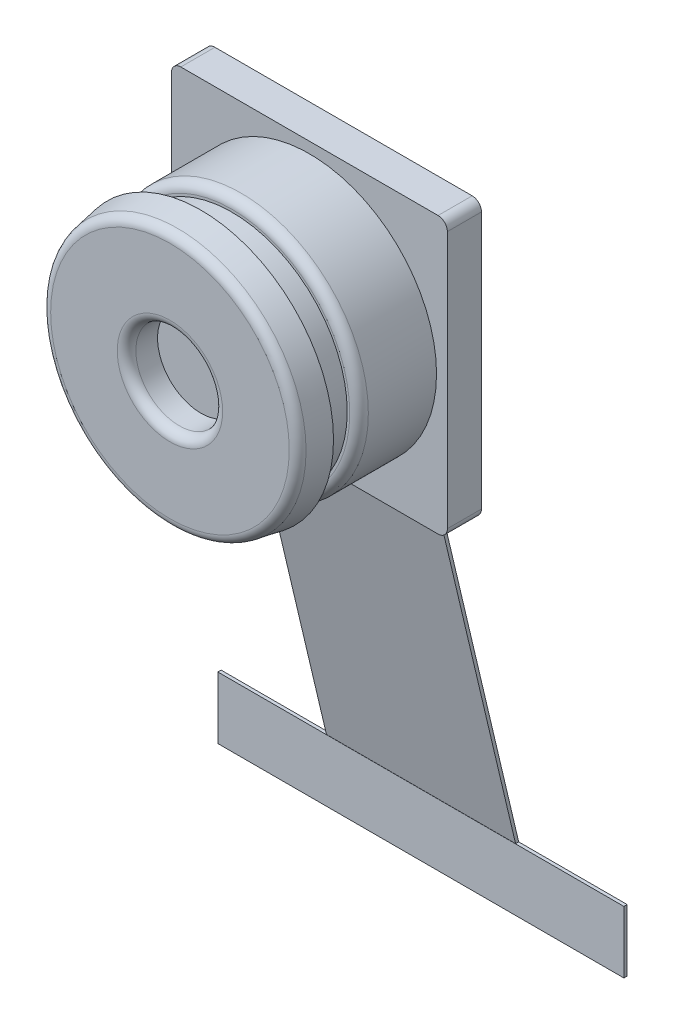
SolidWorks part; units mm, degrees
ref_plane "前视基准面" through (0, 0, 0) normal (0, 0, 1) x (1, 0, 0)
ref_plane "上视基准面" through (0, 0, 0) normal (0, 1, 0) x (1, 0, 0)
ref_plane "右视基准面" through (0, 0, 0) normal (1, 0, 0) x (0, 0, -1)
sketch "草图1" plane through (0, 0, 0) normal (0, 0, 1) x (1, 0, 0)
  line L0 (2.654, -2.67) -> (4.054, -2.67)
  line L1 (-4.846, 6.23) -> (4.054, 6.23)
  line L2 (-4.846, 6.23) -> (-4.846, -2.67)
  line L3 (-4.846, -2.67) -> (-3.446, -2.67)
  line L4 (4.054, 6.23) -> (4.054, -2.67)
  line L5 (-4.846, 6.23) -> (4.054, -2.67) construction
  line L6 (-4.846, -2.67) -> (4.054, 6.23) construction
  line L8 (-3.446, -2.67) -> (-3.446, -13.67)
  line L10 (2.654, -2.67) -> (2.654, -13.67)
  line L11 (-3.446, -2.67) -> (2.654, -13.67) construction
  line L12 (-3.446, -13.67) -> (2.654, -2.67) construction
  line L13 (-6.946, -13.67) -> (-3.446, -13.67)
  line L14 (-6.946, -13.67) -> (-6.946, -15.67)
  line L15 (-6.946, -15.67) -> (6.154, -15.67)
  line L16 (6.154, -13.67) -> (6.154, -15.67)
  line L17 (-6.946, -13.67) -> (6.154, -15.67) construction
  line L18 (-6.946, -15.67) -> (6.154, -13.67) construction
  line L19 (2.654, -13.67) -> (6.154, -13.67)
  point P4 (-0.396, 1.78)
  point P9 (-0.396, -8.17)
  point P14 (-0.396, -14.67)
  dimension "D1" = 8.9
  dimension "D2" = 8.9
  dimension "D3" = 11
  dimension "D4" = 1.4
  dimension "D5" = 1.4
  dimension "D6" = 3.5
  dimension "D7" = 3.5
  dimension "D8" = 2
extrude "底面" add sketch "草图1" along normal blind 0.1
sketch "草图2" plane through (0, 0, 0.1) normal (0, 0, 1) x (1, 0, 0)
  line L1 (-4.846, 6.23) -> (4.054, 6.23)
  line L2 (-4.846, 6.23) -> (-4.846, -2.67)
  line L3 (-4.846, -2.67) -> (4.054, -2.67)
  line L4 (4.054, 6.23) -> (4.054, -2.67)
  line L5 (-4.846, 6.23) -> (4.054, -2.67) construction
  line L6 (-4.846, -2.67) -> (4.054, 6.23) construction
  point P4 (-0.396, 1.78)
extrude "凸台-拉伸2" add sketch "草图2" along normal blind 1
sketch "草图3" plane through (0, 0, 1.1) normal (0, 0, 1) x (1, 0, 0)
  circle A0 centre (-0.396, 1.78) radius 4.1
  dimension "D1" = 8.2
extrude "凸台-拉伸3" add sketch "草图3" along normal blind 2.5
sketch "草图4" plane through (0, 0, 3.6) normal (0, 0, 1) x (1, 0, 0)
  circle A0 centre (-0.396, 1.78) radius 3.7191
extrude "凸台-拉伸4" add sketch "草图4" along normal blind 2
sketch "草图5" plane through (0, 0, 5.6) normal (0, 0, 1) x (1, 0, 0)
  circle A0 centre (-0.396, 1.78) radius 4.1
  dimension "D1" = 8.2
extrude "凸台-拉伸5" add sketch "草图5" against normal blind 1 draft 10 draft outward yes
sketch "草图6" plane through (0, 0, 5.6) normal (0, 0, 1) x (1, 0, 0)
  circle A0 centre (-0.396, 1.78) radius 1.4
  dimension "D1" = 2.8
extrude "切除-拉伸1" cut sketch "草图6" against normal blind 1
fillet "圆角1" radius 0.3 2 edges at (3.704, 1.78, 3.6) (3.704, 1.78, 5.6)
fillet "圆角2" radius 0.3 4 edges at (4.054, 6.23, 0.55) (4.054, -2.67, 0.55) (-4.846, -2.67, 0.55) (-4.846, 6.23, 0.55)
fillet "圆角3" radius 0.3 1 edges at (1.004, 1.78, 5.6)
sketch "草图11" plane through (0, 0, 0) normal (0, 0, -1) x (-1, 0, 0)
  line L0 (-2.654, -13.67) -> (-6.154, -13.67)
  line L1 (3.446, -2.67) -> (-2.654, -2.67)
  line L2 (3.446, -2.67) -> (3.446, -13.67)
  line L4 (-2.654, -2.67) -> (-2.654, -13.67)
  line L5 (3.446, -2.67) -> (-2.654, -13.67) construction
  line L6 (3.446, -13.67) -> (-2.654, -2.67) construction
  line L7 (6.946, -13.67) -> (3.446, -13.67)
  line L8 (6.946, -13.67) -> (6.946, -15.67)
  line L9 (6.946, -15.67) -> (-6.154, -15.67)
  line L10 (-6.154, -13.67) -> (-6.154, -15.67)
  line L11 (6.946, -13.67) -> (-6.154, -15.67) construction
  line L12 (6.946, -15.67) -> (-6.154, -13.67) construction
  point P4 (0.396, -8.17)
  point P11 (0.396, -14.67)
extrude "凸台-拉伸7" add sketch "草图11" along normal blind 2.6 and the other way blind 0.1
sketch "草图12" plane through (-3.446, 0, 0) normal (-1, 0, 0) x (0, 0, 1)
  line L0 (0, -2.67) -> (-2.6, -13.67)
  line L1 (0, -2.67) -> (-2.6, -2.67) construction
  line L2 (0, -2.37) -> (0, -2.67) construction
  line L3 (-2.6, -13.67) -> (-2.6, -2.67)
  line L4 (-2.6, -2.67) -> (0, -2.67)
  line L5 (0.1, -2.67) -> (-2.5, -13.67)
  line L6 (0.1, -13.67) -> (-2.6, -13.67) construction
  line L7 (-2.5, -13.67) -> (0.1, -13.67)
  line L8 (0.1, -13.67) -> (0.1, -2.67)
extrude "切除-拉伸4" cut sketch "草图12" against normal up to next
sketch "草图13" plane through (-6.946, 0, 0) normal (-1, 0, 0) x (0, 0, 1)
  line L0 (0.1, -13.67) -> (-2.6, -13.67) construction
  line L1 (0.1, -15.67) -> (-2.4941, -15.67)
  line L2 (0.1, -15.67) -> (0.1, -13.67)
  line L3 (0.1, -13.67) -> (-2.4941, -13.67)
  line L4 (-2.4941, -15.67) -> (-2.4941, -13.67)
  line L5 (0.1, -15.67) -> (-2.4941, -13.67) construction
  line L6 (0.1, -13.67) -> (-2.4941, -15.67) construction
  point P4 (-1.197, -14.67)
extrude "切除-拉伸5" cut sketch "草图13" against normal up to next
